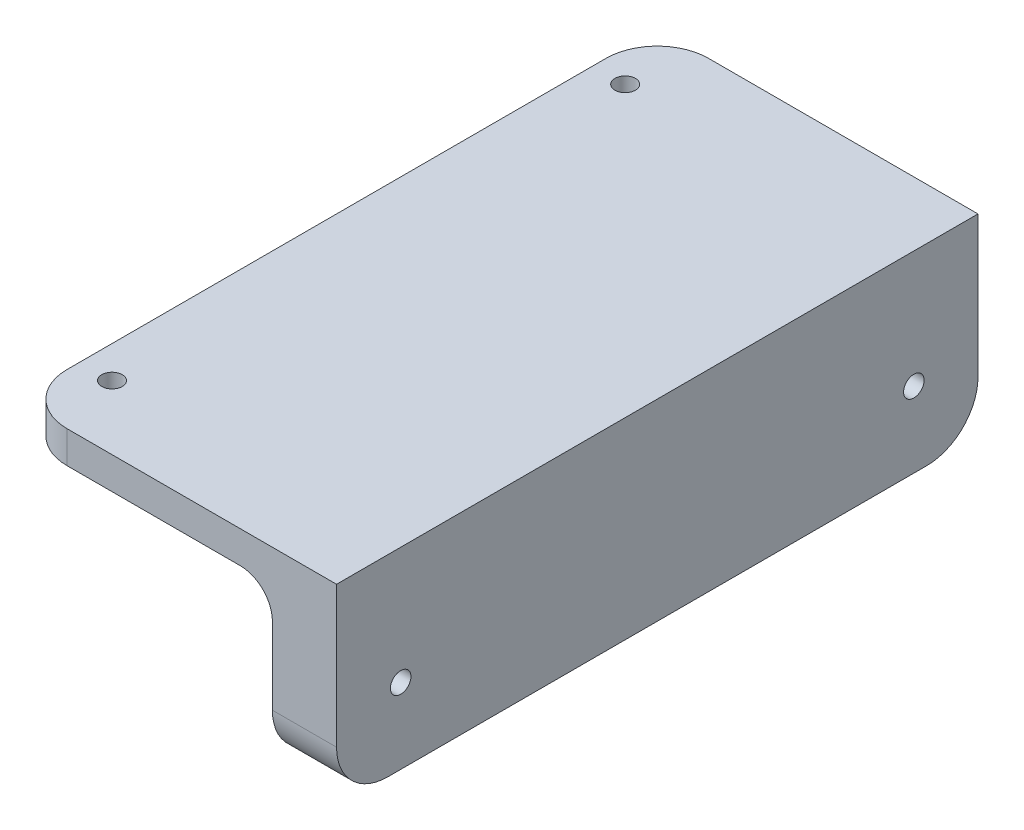
SolidWorks part; units mm, degrees
ref_plane "Alzado" through (0, 0, 0) normal (0, 0, 1) x (1, 0, 0)
ref_plane "Planta" through (0, 0, 0) normal (0, 1, 0) x (1, 0, 0)
ref_plane "Vista lateral" through (0, 0, 0) normal (1, 0, 0) x (0, 0, -1)
sketch "Croquis1" plane through (0, 0, 0) normal (0, 1, 0) x (1, 0, 0)
  line L1 (0, 0) -> (50, 0)
  line L2 (0, 0) -> (0, -100)
  line L3 (0, -100) -> (50, -100)
  line L4 (50, 0) -> (50, -100)
  circle A0 centre (5, -10) radius 1.6
  circle A1 centre (5, -90) radius 1.6
  point P9 (0, 0)
  dimension "D6" = 3.2
  dimension "D7" = 3.2
  dimension "D1" = 50
  dimension "D2" = 100
  dimension "D3" = 80
  dimension "D4" = 10
  dimension "D5" = 45
extrude "Saliente-Extruir1" add sketch "Croquis1" along normal blind 5
sketch "Croquis2" plane through (0, 0, 0) normal (0, -1, 0) x (1, 0, 0)
  line L0 (0, 100) -> (50, 100) construction
  line L1 (50, 0) -> (40, 0)
  line L2 (50, 0) -> (50, 100)
  line L3 (50, 100) -> (40, 100)
  line L4 (40, 0) -> (40, 100)
  dimension "D1" = 10
extrude "Saliente-Extruir2" add sketch "Croquis2" along normal blind 25
sketch "Croquis3" plane through (40, 0, 0) normal (-1, 0, 0) x (0, 0, 1)
  line L0 (0, -13.25) -> (100, -13.25) construction
  line L1 (0, -25) -> (0, 0) construction
  line L2 (100, -25) -> (100, 0) construction
  line L3 (100, 0) -> (0, 0) construction
  circle A0 centre (10, -13.25) radius 1.6
  circle A1 centre (90, -13.25) radius 1.6
  dimension "D2" = 3.2
  dimension "D3" = 3.2
  dimension "D1" = 13.25
  dimension "D4" = 10
  dimension "D5" = 10
extrude "Cortar-Extruir1" cut sketch "Croquis3" against normal up to surface (10 mm away) up to face at (50, -10, 50)
sketch "Croquis4" plane through (0, 0, 0) normal (0, -1, 0) x (1, 0, 0)
  line L0 (40, 0) -> (0, 0) construction
  line L1 (3.3257, 7.1) -> (6.6743, 7.1)
  line L2 (6.6743, 7.1) -> (8.3486, 10)
  line L3 (8.3486, 10) -> (6.6743, 12.9)
  line L4 (6.6743, 12.9) -> (3.3257, 12.9)
  line L5 (3.3257, 12.9) -> (1.6514, 10)
  line L6 (1.6514, 10) -> (3.3257, 7.1)
  line L7 (3.3257, 87.1) -> (6.6743, 87.1)
  line L8 (6.6743, 87.1) -> (8.3486, 90)
  line L9 (8.3486, 90) -> (6.6743, 92.9)
  line L10 (6.6743, 92.9) -> (3.3257, 92.9)
  line L11 (3.3257, 92.9) -> (1.6514, 90)
  line L12 (1.6514, 90) -> (3.3257, 87.1)
  line L13 (0, 100) -> (40, 100) construction
  circle A0 centre (5, 10) radius 2.9 construction
  circle A1 centre (5, 90) radius 2.9 construction
  dimension "D1" = 5.8
  dimension "D2" = 5.8
extrude "Cortar-Extruir2" cut sketch "Croquis4" against normal blind 1
fillet "Redondeo1" radius 8 4 edges at (0, 2.5, 100) (45, -25, 100) (0, 2.5, 0) (45, -25, 0)
sketch "Croquis5" plane through (40, 0, 0) normal (-1, 0, 0) x (0, 0, 1)
  line L0 (100, 0) -> (0, 0) construction
  line L1 (20, 0) -> (80, 0)
  line L2 (20, 0) -> (20, -15)
  line L3 (20, -15) -> (80, -15)
  line L4 (80, 0) -> (80, -15)
  circle A0 centre (10, -13.25) radius 1.6 construction
  dimension "D1" = 60
  dimension "D2" = 10
  dimension "D3" = 15
extrude "Saliente-Extruir3" add sketch "Croquis5" along normal blind 30
fillet "Redondeo2" radius 5 10 edges at (40, -15, 50) (40, 0, 90) (40, 0, 10) (10, -15, 50) (40, -7.5, 80) (25, -15, 80) (25, 0, 80) (10, 0, 50) (40, -7.5, 20) (25, 0, 20)
sketch "Croquis6" plane through (40, 0, 0) normal (-1, 0, 0) x (0, 0, 1)
  circle A0 centre (10, -13.25) radius 2.8
  circle A1 centre (90, -13.25) radius 2.8
  dimension "D1" = 5.6
  dimension "D2" = 5.6
extrude "Cortar-Extruir3" cut sketch "Croquis6" against normal blind 1.5
